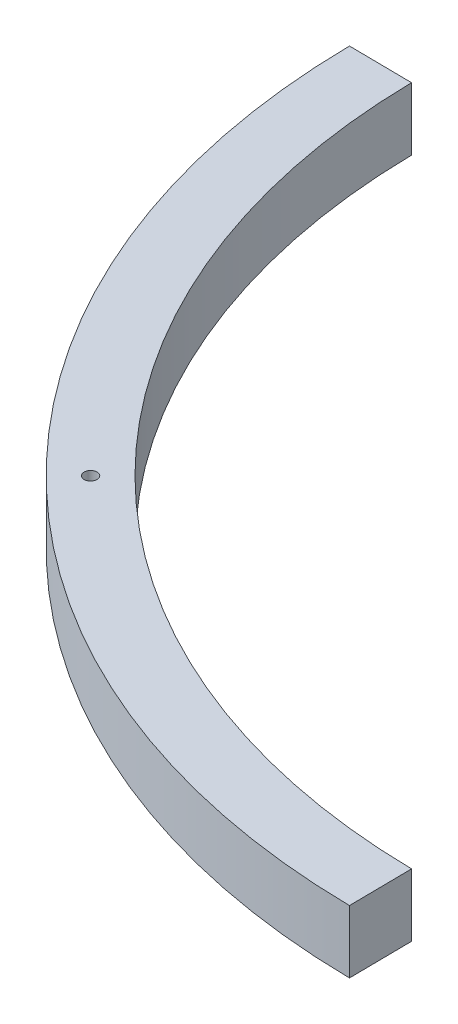
SolidWorks part; units mm, degrees
ref_plane "Front Plane" through (0, 0, 0) normal (0, 0, 1) x (1, 0, 0)
ref_plane "Top Plane" through (0, 0, 0) normal (0, 1, 0) x (1, 0, 0)
ref_plane "Right Plane" through (0, 0, 0) normal (1, 0, 0) x (0, 0, -1)
sketch "Sketch1" plane through (0, 0, 0) normal (0, 1, 0) x (1, 0, 0)
  line L0 (-90, 87.9228) -> (-74.9847, 87.75)
  line L1 (-90, -90) -> (90, -90) construction
  line L2 (-90, -90) -> (-90, 90) construction
  line L3 (-90, 90) -> (90, 90) construction
  line L4 (90, -90) -> (90, 90) construction
  line L5 (-90, -90) -> (90, 90) construction
  line L6 (-90, 90) -> (90, -90) construction
  line L15 (87.9228, -90) -> (87.7483, -74.9846)
  arc A0 (-90, 87.9228) -> (87.9228, -90) centre (90, 90) ccw
  arc A1 (-74.9847, 87.75) -> (87.7483, -74.9846) centre (90, 90) ccw
  arc A2 (-82.5, 90) -> (90, -82.5) centre (90, 90) ccw construction
  circle A6 centre (-31.9759, -31.9759) radius 1.55
  point P0 (0, 0)
  point P8 (90, -70)
  point P9 (-70, 90)
  dimension "D2" = 330
  dimension "D3" = 345
  dimension "D4" = 3.1
  dimension "D1" = 180
extrude "Boss-Extrude1" add sketch "Sketch1" along normal blind 15
